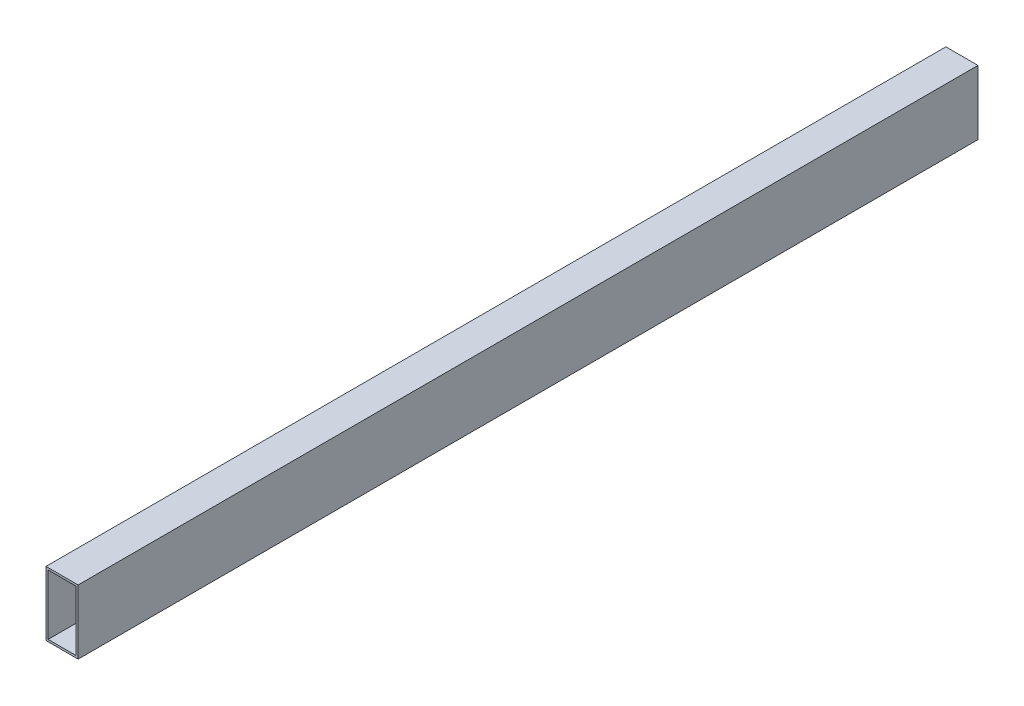
SolidWorks part; units mm, degrees
material "6061 Alloy"
ref_plane "Front Plane" through (0, 0, 0) normal (0, 0, 1) x (1, 0, 0)
ref_plane "Top Plane" through (0, 0, 0) normal (0, 1, 0) x (1, 0, 0)
ref_plane "Right Plane" through (0, 0, 0) normal (1, 0, 0) x (0, 0, -1)
sketch "Sketch1" plane through (0, 0, 0) normal (0, 0, 1) x (1, 0, 0)
  line L1 (-48.4372, -30.1994) -> (-23.0372, -30.1994)
  line L2 (-48.4372, -30.1994) -> (-48.4372, 20.6006)
  line L3 (-48.4372, 20.6006) -> (-23.0372, 20.6006)
  line L4 (-23.0372, -30.1994) -> (-23.0372, 20.6006)
  dimension "D1" = 25.4
  dimension "D2" = 50.8
extrude "Boss-Extrude1" add sketch "Sketch1" along normal blind 711.2
sketch "Sketch2" plane through (0, 0, 711.2) normal (0, 0, 1) x (1, 0, 0)
  line L0 (-48.4372, 20.6006) -> (-48.4372, -30.1994) construction
  line L1 (-46.7862, 18.9496) -> (-24.6882, 18.9496)
  line L2 (-46.7862, 18.9496) -> (-46.7862, -28.5484)
  line L3 (-46.7862, -28.5484) -> (-24.6882, -28.5484)
  line L4 (-24.6882, 18.9496) -> (-24.6882, -28.5484)
  line L5 (-46.7862, 18.9496) -> (-24.6882, -28.5484) construction
  line L6 (-46.7862, -28.5484) -> (-24.6882, 18.9496) construction
  line L7 (-23.0372, -30.1994) -> (-23.0372, 20.6006) construction
  line L8 (-23.0372, 20.6006) -> (-48.4372, 20.6006) construction
  line L9 (-48.4372, -30.1994) -> (-23.0372, -30.1994) construction
  point P0 (-35.7372, -4.7994)
  dimension "D1" = 1.651
  dimension "D2" = 1.651
  dimension "D3" = 1.651
  dimension "D4" = 1.651
extrude "Cut-Extrude1" cut sketch "Sketch2" against normal through all
ref_plane "Midplane" through (0, 0, 355.6) normal (0, 0, 1) x (1, 0, 0)
